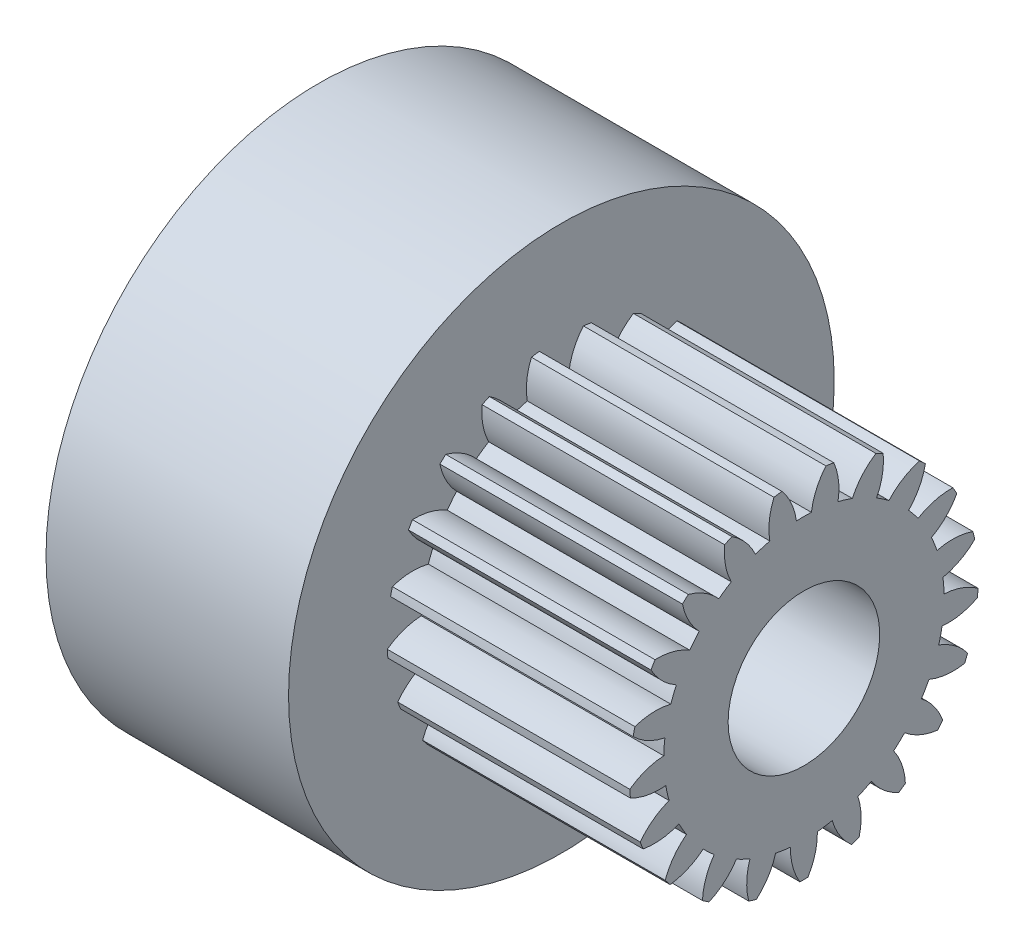
SolidWorks part; units mm, degrees
ref_plane "Plane1" through (0, 0, 0) normal (0, 0, 1) x (1, 0, 0)
ref_plane "Plane2" through (0, 0, 0) normal (0, 1, 0) x (1, 0, 0)
ref_plane "Plane3" through (0, 0, 0) normal (1, 0, 0) x (0, 0, -1)
sketch "HoldingSke" plane through (0, 0, 0) normal (0, 1, 0) x (1, 0, 0)
  line L0 (0, 0) -> (1.8672, -0.7167)
  line L1 (-15, 0) -> (100, 0) construction
  line L2 (0, 0) -> (-2.1039, 2.3779)
  line L3 (0, 0) -> (-11.863, 4.5341)
  line L4 (0, 0) -> (8.0624, 3.0949)
  line L5 (0, 0) -> (-14.9912, -5.5913)
  line L6 (0, 0) -> (-6.6317, -4.4744)
  line L7 (-2.1039, 2.3779) -> (1.3401, 18.0029)
  line L8 (-76.2, 54.61) -> (-75.3, 54.61)
  line L9 (-71.009, 38.7566) -> (-53.1078, 45.2721)
  line L10 (-76.2, 71.12) -> (104.1128, 71.12)
  line L11 (0, 0) -> (-8, 0)
  line L12 (-76.2, 101.6) -> (-76.181, 101.6)
  line L13 (24.9733, 27.94) -> (52.9518, 28.4284)
  line L14 (24.9733, 27.94) -> (24.9743, 27.94)
  line L15 (24.9733, 27.94) -> (100.4006, 29.5858)
  line L16 (-63.627, -0.5) -> (-12.827, -0.5)
  circle A0 centre (0, 0) radius 2.5
  circle A1 centre (0, 0) radius 4.624
  circle A2 centre (0, 0) radius 8
  circle A3 centre (0, 0) radius 2.5
  dimension "MHD" = 9.248
  dimension "Hub_dia" = 16
  dimension "Bore" = 5
  dimension "MBD" = 5
  dimension "Num_teeth" = 21
  dimension "Pitch" = 2
  dimension "Overall_len" = 16
  dimension "Show_teeth" = 21
  dimension "Thickness" = 8
  dimension "OAL" = 16.0001
  dimension "T_dim" = 0.9
  dimension "Ap" = 20
  dimension "H" = 19.05
  dimension "Pitch_radius" = 180.3128
  dimension "Width" = 8
  dimension "Backlash" = 0.019
  dimension "Addendum_fac" = 1
  dimension "Dedendum_fac" = 1.25
  dimension "Clearance_fac" = 0.25
  dimension "Dedendum_add" = 0.001
  dimension "Module" = 0.5
sketch "BasProSke" plane through (0, 0, 0) normal (0, 1, 0) x (1, 0, 0)
  line L0 (-10, 0) -> (60, 0) construction
  line L1 (0, 0) -> (0, 5.75)
  line L2 (0, 0) -> (8, 0)
  line L3 (8, 0) -> (8, 5.75)
  line L4 (8, 5.75) -> (0, 5.75)
  dimension "Thickness" = 8
  dimension "Diameter" = 11.5
revolve "Base-Revolve" add sketch "BasProSke" angle 360 about L0
sketch "TooCutSke" plane through (0, 0, 0) normal (1, 0, 0) x (0, 0, -1)
  line L1 (0, 0) -> (0, 107) construction
  line L2 (0, 0) -> (-0.4256, 5.2327) construction
  line L3 (0, 0) -> (-1.5613, 10.3584) construction
  line L4 (-0.4256, 5.2327) -> (-0.7806, 5.1792) construction
  arc A0 (0.2476, 4.6174) -> (-0.2476, 4.6174) centre (0, 0) ccw
  arc A1 (0.7462, 5.727) -> (-0.7462, 5.727) centre (0, 0) ccw
  circle A2 centre (0, 0) radius 5.25 construction
  circle A3 centre (0, 0) radius 4.9334 construction
  arc A4 (-0.2476, 4.6174) -> (-0.7462, 5.727) centre (-2.3303, 4.3484) ccw
  arc A5 (0.7462, 5.727) -> (0.2476, 4.6174) centre (2.3303, 4.3484) ccw
  dimension "Root_dia" = 9.248
  dimension "Overcut_dia" = 11.5508
  dimension "Pitch_dia" = 10.5
  dimension "Base_dia" = 9.8668
  dimension "Flank_rad" = 2.1
  dimension "Half_ang" = 8.571
  dimension "Half_CT" = 0.3591
extrude "ToothCut" cut sketch "TooCutSke" along normal through all
fillet "Breaks" [suppressed] radius 0.01
fillet "RootFillets" [suppressed] radius 0.126
pattern_circular "TeethCuts" count 21 every 17.143 about axis through (-10, 0, 0) along (1, 0, 0) of "ToothCut", "RootFillets", "Breaks"
sketch "HubNeaOneSke" plane through (0, 0, 0) normal (-1, 0, 0) x (0, 0, 1)
  circle A0 centre (0, 0) radius 4.624
  dimension "Diameter" = 9.248
extrude "HubNearOne" add sketch "HubNeaOneSke" along normal blind 8.0001
sketch "HubNeaBotSke" plane through (0, 0, 0) normal (-1, 0, 0) x (0, 0, 1)
  circle A0 centre (0, 0) radius 4.624
  dimension "Diameter" = 9.248
extrude "HubNearBoth" [suppressed] add sketch "HubNeaBotSke" along normal blind 4
ref_plane "FarPln" through (8, 0, 0) normal (1, 0, 0) x (0, 0, -1)
sketch "HubFarSke" plane through (8, 0, 0) normal (1, 0, 0) x (0, 0, -1)
  circle A0 centre (0, 0) radius 4.624
  dimension "Diameter" = 9.248
extrude "HubFar" [suppressed] add sketch "HubFarSke" along normal blind 4
sketch "BorSke" plane through (0, 0, 0) normal (1, 0, 0) x (0, 0, -1)
  circle A0 centre (0, 0) radius 2.5
  dimension "Diameter" = 5
extrude "Bore" cut sketch "BorSke" along normal mid plane 32.0001
sketch "KeySke" plane through (0, 0, 0) normal (1, 0, 0) x (0, 0, -1)
  line L0 (-1, 0) -> (-1, 3.4)
  line L1 (-1, 3.4) -> (1, 3.4)
  line L2 (1, 3.4) -> (1, 0)
  line L3 (0, 0) -> (0, 34) construction
  line L4 (-1, 0) -> (1, 0)
  dimension "Offset" = 3.4
  dimension "Width" = 2
extrude "Keyway" [suppressed] cut sketch "KeySke" along normal mid plane 32.0001
pattern_circular "Keyway2" [suppressed] count 2 every 90 about axis through (-10, 0, 0) along (1, 0, 0)
sketch "Sketch1" plane through (-8.0001, 0, 0) normal (-1, 0, 0) x (0, 0, 1)
  circle A0 centre (0, 0) radius 4.624 construction
  circle A1 centre (0, 0) radius 4.624
  circle A2 centre (0, 0) radius 9
  dimension "D1" = 18
extrude "Boss-Extrude1" add sketch "Sketch1" against normal up to surface (8.0001 mm away) up to face at (0, 3.8064, -3.5318)
sketch "Sketch3" plane through (0, 0, 0) normal (0, 1, 0) x (1, 0, 0)
  line L0 (-8.0001, 0) -> (0, 0) construction
  line L1 (-8.0001, 9) -> (-8.0001, -9) construction
  line L2 (0, -9) -> (0, 9) construction
  line L4 (-2.5001, -2.75) -> (-8.0001, -2.75) construction
  line L5 (-2.5001, -2.75) -> (-2.5001, 2.75) construction
  line L6 (-2.5001, 2.75) -> (-8.0001, 2.75) construction
  line L7 (-8.0001, -2.75) -> (-8.0001, 2.75) construction
  line L8 (-2.5001, -2.75) -> (-8.0001, 2.75) construction
  line L9 (-2.5001, 2.75) -> (-8.0001, -2.75) construction
  circle A0 centre (-5.2501, 0) radius 1.8
  point P12 (-8.0001, 2.75)
  dimension "D1" = 3.6
  dimension "D2" = 5.5
extrude "Cut-Extrude1" cut sketch "Sketch3" against normal through all
sketch "Sketch4" plane through (-8.0001, 0, 0) normal (-1, 0, 0) x (0, 0, 1)
  line L1 (-2.75, -6.1) -> (2.75, -6.1)
  line L2 (-2.75, -6.1) -> (-2.75, -3.9)
  line L3 (-2.75, -3.9) -> (2.75, -3.9)
  line L4 (2.75, -6.1) -> (2.75, -3.9)
  line L5 (-2.75, -6.1) -> (2.75, -3.9) construction
  line L6 (-2.75, -3.9) -> (2.75, -6.1) construction
  circle A0 centre (0, 0) radius 2.5 construction
  point P0 (0, -5)
  point P5 (0, 0)
  point P6 (0, 0)
  dimension "D1" = 5.5
  dimension "D2" = 2.2
  dimension "D3" = 2.5
extrude "Cut-Extrude2" cut sketch "Sketch4" against normal blind 5.5
equation "' \"Module@HoldingSke\" = 6.35"
equation "' \"Num_teeth@HoldingSke\" = 12"
equation "' \"Ap@HoldingSke\" =  20"
equation "' \"Ap@HoldingSke\" = 20"
equation "' \"Width@HoldingSke\" = 0.5 * 25.4"
equation "' \"Hub_dia@HoldingSke\"= 1 * 25.4"
equation "' \"Hub_dia@HoldingSke\" = 1 * 25.4"
equation "' \"Overall_len@HoldingSke\" = 1.0 * 25.4"
equation "' \"Bore@HoldingSke\" = 0.75 * 25.4"
equation "' \"T_dim@HoldingSke\" = 0.1 * 25.4"
equation "' \"Width@KeySke\" = 0.25 * 25.4"
equation "' \"Show_teeth@HoldingSke\" = 13"
equation "' \"Backlash@HoldingSke\" = 0.009 * 25.4"
equation "' \"Addendum_fac@HoldingSke\" = 1.0"
equation "' \"Dedendum_fac@HoldingSke\" = 1.25"
equation "' \"Dedendum_add@HoldingSke\" = 0.00005 * 25.4"
equation "' \"Clearance_fac@HoldingSke\" = 0.25"
equation "\"Pitch@HoldingSke\" = 1 / \"Module@HoldingSke\""
equation "\"Overcut_dia@TooCutSke\" = (\"Num_teeth@HoldingSke\" + 2 * \"Addendum_fac@HoldingSke\") / \"Pitch@HoldingSke\" + 0.002 * 25.4"
equation "\"Pitch_dia@TooCutSke\" = \"Num_teeth@HoldingSke\" / \"Pitch@HoldingSke\""
equation "\"Base_dia@TooCutSke\" = \"Num_teeth@HoldingSke\" / \"Pitch@HoldingSke\" * cos((\"Ap@HoldingSke\"  * 3.14159265 / 180))"
equation "\"Root_dia@TooCutSke\" = (\"Num_teeth@HoldingSke\" + 2) / \"Pitch@HoldingSke\" - 2 * (\"Addendum_fac@HoldingSke\" + \"Dedendum_fac@HoldingSke\") / \"Pitch@HoldingSke\" - \"Dedendum_add@HoldingSke\" * 2"
equation "\"Half_ang@TooCutSke\" = 180 / \"Num_teeth@HoldingSke\""
equation "\"Half_CT@TooCutSke\" = \"Num_teeth@HoldingSke\" / \"Pitch@HoldingSke\" * sin((3.14159265 / 2 / \"Num_teeth@HoldingSke\")) / 2 - 7 * \"Backlash@HoldingSke\" / 4"
equation "\"Flank_rad@TooCutSke\" = \"Num_teeth@HoldingSke\" / \"Pitch@HoldingSke\" / 5"
equation "\"Radius@RootFillets\" = \"Clearance_fac@HoldingSke\" / \"Pitch@HoldingSke\" + \"Dedendum_add@HoldingSke\""
equation "\"Break_rad@Breaks\" = 0.02 / \"Pitch@HoldingSke\""
equation "\"Thickness@HoldingSke\" = \"Width@HoldingSke\""
equation "\"OAL@HoldingSke\" = \"Thickness@HoldingSke\""
equation "\"MHD@HoldingSke\" = (\"Num_teeth@HoldingSke\" + 2) / \"Pitch@HoldingSke\" - 2 * (\"Addendum_fac@HoldingSke\" + \"Dedendum_fac@HoldingSke\")  / \"Pitch@HoldingSke\" - \"Dedendum_add@HoldingSke\" * 2"
equation "\"MBD@HoldingSke\" = (\"Num_teeth@HoldingSke\" + 2) / \"Pitch@HoldingSke\" - 2 * (\"Addendum_fac@HoldingSke\" + \"Dedendum_fac@HoldingSke\")  / \"Pitch@HoldingSke\" - \"Dedendum_add@HoldingSke\" * 2 - 0.002 * 25.4"
equation "\"MHD@HoldingSke\" = ((sgn( \"MHD@HoldingSke\" - \"Hub_dia@HoldingSke\" )-1)*( \"MHD@HoldingSke\" - \"Hub_dia@HoldingSke\" ))/-2+ \"Hub_dia@HoldingSke\""
equation "\"MBD@HoldingSke\" = ((sgn( \"MBD@HoldingSke\" - \"Bore@HoldingSke\" )-1)*( \"MBD@HoldingSke\" - \"Bore@HoldingSke\" ))/-2+ \"Bore@HoldingSke\""
equation "\"OAL@HoldingSke\" = ((sgn( \"OAL@HoldingSke\" - \"Overall_len@HoldingSke\" )+1)*( \"OAL@HoldingSke\" - \"Overall_len@HoldingSke\" ))/2 + \"Overall_len@HoldingSke\" + 0.000002 * 25.4"
equation "\"Num_teeth@TeethCuts\" = int( \"Show_teeth@HoldingSke\" ) + 1"
equation "\"Num_teeth@TeethCuts\" = ((sgn( \"Num_teeth@TeethCuts\" - \"Num_teeth@HoldingSke\" )-1)*( \"Num_teeth@TeethCuts\" - \"Num_teeth@HoldingSke\" ))/-2+ \"Num_teeth@HoldingSke\""
equation "\"Num_teeth@TeethCuts\" = ((sgn( \"Num_teeth@TeethCuts\" - 2.0)+1)*( \"Num_teeth@TeethCuts\" - 2.0))/2 +2.0"
equation "\"Angle@TeethCuts\" = 360.0 / \"Num_teeth@HoldingSke\""
equation "\"Diameter@BasProSke\" = (\"Num_teeth@HoldingSke\" + 2 * \"Addendum_fac@HoldingSke\") / \"Pitch@HoldingSke\""
equation "\"Thickness@BasProSke\"  = \"Thickness@HoldingSke\""
equation "' \"Fillet_rad@BasProSke\" =  \"Thickness@HoldingSke\" * 0.05"
equation "' \"Fillet_rad@BasProSke\" = \"Thickness@HoldingSke\" * 0.05"
equation "\"MHD@HoldingSke\" = ((sgn( \"MHD@HoldingSke\" - \"Root_dia@TooCutSke\" )-1)*( \"MHD@HoldingSke\" - \"Root_dia@TooCutSke\" ))/-2+ \"Root_dia@TooCutSke\""
equation "\"Diameter@HubNeaOneSke\" = \"MHD@HoldingSke\""
equation "\"Length@HubNearOne\" = \"OAL@HoldingSke\" - \"Thickness@BasProSke\""
equation "\"Diameter@HubNeaBotSke\" = \"MHD@HoldingSke\""
equation "\"Length@HubNearBoth\" = ( \"OAL@HoldingSke\" - \"Thickness@BasProSke\" ) / 2.0"
equation "\"Thickness@FarPln\" = \"Thickness@BasProSke\""
equation "\"Diameter@HubFarSke\" = \"MHD@HoldingSke\""
equation "\"Length@HubFar\" = ( \"OAL@HoldingSke\" - \"Thickness@BasProSke\" ) / 2.0"
equation "\"Diameter@BorSke\" = \"MBD@HoldingSke\""
equation "\"D1@Bore\" = \"OAL@HoldingSke\" * 2.0"
equation "\"D1@Keyway\" = \"OAL@HoldingSke\" * 2.0"
equation "\"Offset@KeySke\" = \"T_dim@HoldingSke\" + \"MBD@HoldingSke\" / 2.0"
